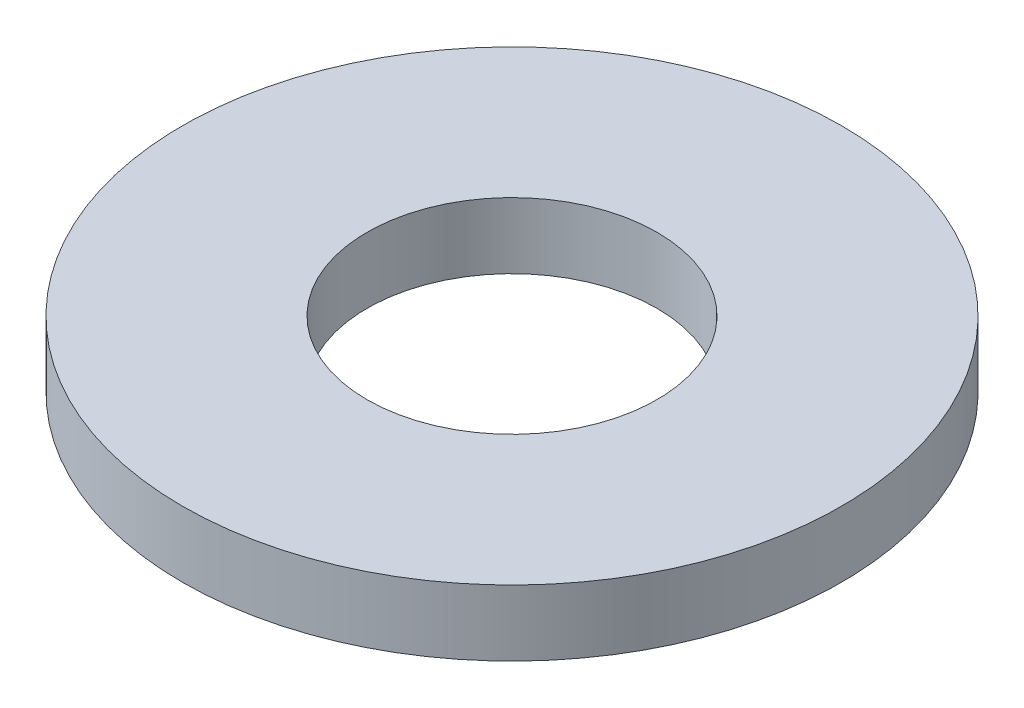
SolidWorks part; units mm, degrees
material "AISI Acier inoxydable type 316L"
ref_plane "Plan de face" through (0, 0, 0) normal (0, 0, 1) x (1, 0, 0)
ref_plane "Plan de dessus" through (0, 0, 0) normal (0, 1, 0) x (1, 0, 0)
ref_plane "Plan de droite" through (0, 0, 0) normal (1, 0, 0) x (0, 0, -1)
sketch "Esquisse1" plane through (0, 0, 0) normal (0, 1, 0) x (1, 0, 0)
  circle A0 centre (0, 0) radius 1.1
  circle A1 centre (0, 0) radius 2.5
  dimension "D1" = 2.2
  dimension "D2" = 5
extrude "Boss.-Extru.1" add sketch "Esquisse1" along normal mid plane 0.5
